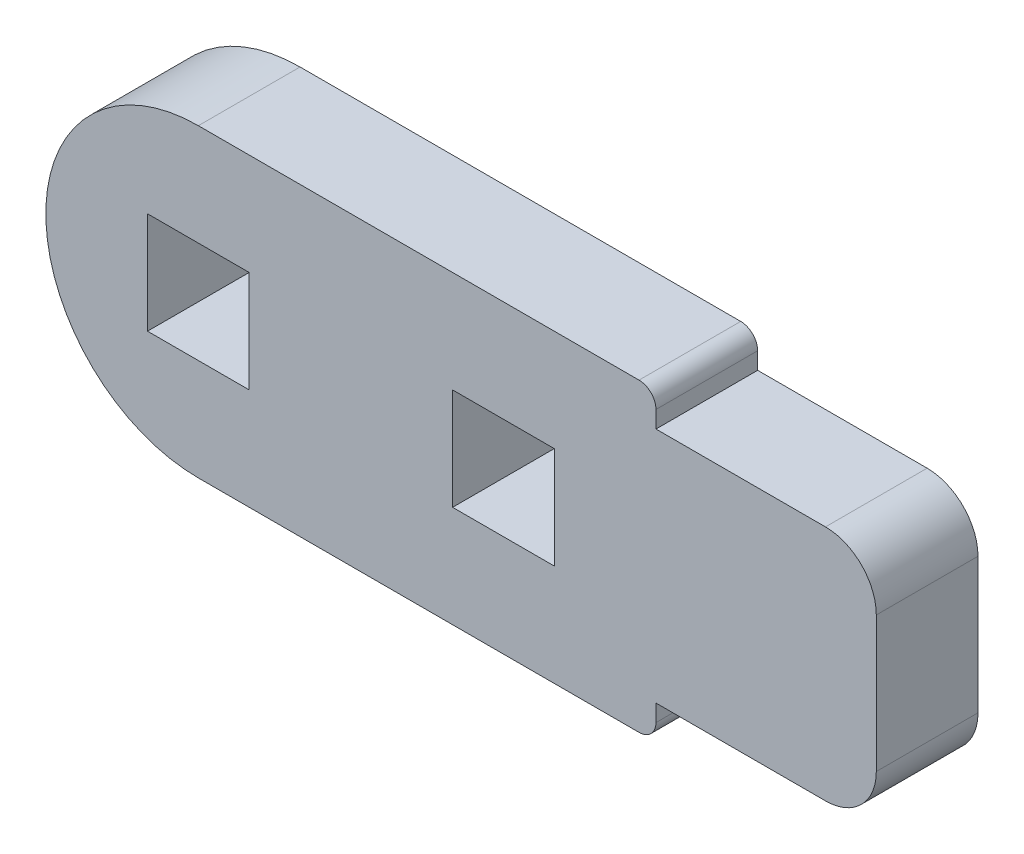
SolidWorks part; units mm, degrees
ref_plane "Alzado" through (0, 0, 0) normal (0, 0, 1) x (1, 0, 0)
ref_plane "Planta" through (0, 0, 0) normal (0, 1, 0) x (1, 0, 0)
ref_plane "Vista lateral" through (0, 0, 0) normal (1, 0, 0) x (0, 0, -1)
sketch "Model" plane through (0, 0, 0) normal (0, 0, 1) x (1, 0, 0)
  line L0 (10.7815, 293.6062) -> (10.7815, 290.6062)
  line L1 (13.7815, 293.6062) -> (10.7815, 293.6062)
  line L2 (13.7815, 290.6062) -> (13.7815, 293.6062)
  line L3 (10.7815, 290.6062) -> (13.7815, 290.6062)
  line L4 (19.7815, 293.6062) -> (19.7815, 290.6062)
  line L5 (22.7815, 293.6062) -> (19.7815, 293.6062)
  line L6 (22.7815, 290.6062) -> (22.7815, 293.6062)
  line L7 (19.7815, 290.6062) -> (22.7815, 290.6062)
  line L8 (25.2815, 296.6062) -> (12.2815, 296.6062)
  line L9 (25.2815, 287.6062) -> (12.2815, 287.6062)
  line L10 (30.7815, 295.6062) -> (25.7815, 295.6062)
  line L11 (25.7815, 288.6062) -> (30.7815, 288.6062)
  line L12 (32.2815, 290.1062) -> (32.2815, 294.1062)
  line L13 (25.7815, 288.6062) -> (25.7815, 288.1062)
  line L14 (25.7815, 296.1062) -> (25.7815, 295.6062)
  arc A0 (32.2815, 294.1062) -> (30.7815, 295.6062) centre (30.7815, 294.1062) ccw
  arc A1 (30.7815, 288.6062) -> (32.2815, 290.1062) centre (30.7815, 290.1062) ccw
  arc A2 (25.7815, 296.1062) -> (25.2815, 296.6062) centre (25.2815, 296.1062) ccw
  arc A3 (25.2815, 287.6062) -> (25.7815, 288.1062) centre (25.2815, 288.1062) ccw
  arc A4 (12.2815, 296.6062) -> (12.2815, 287.6062) centre (12.2815, 292.1062) ccw
extrude "Saliente-Extruir2" add sketch "Model" along normal blind 3
